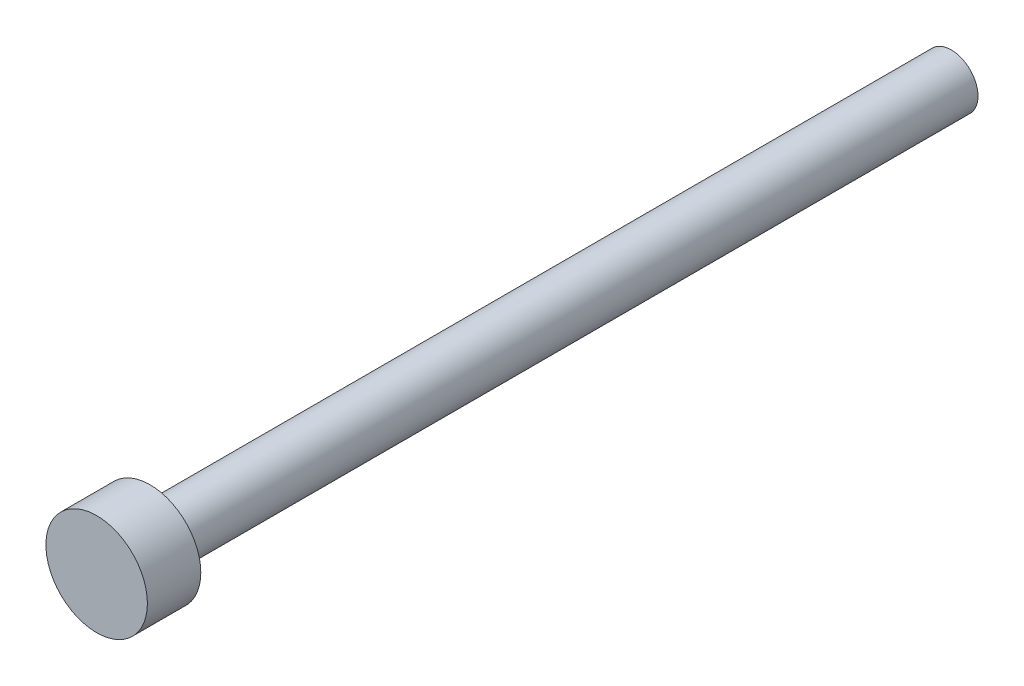
SolidWorks part; units mm, degrees
ref_plane "Front Plane" through (0, 0, 0) normal (0, 0, 1) x (1, 0, 0)
ref_plane "Top Plane" through (0, 0, 0) normal (0, 1, 0) x (1, 0, 0)
ref_plane "Right Plane" through (0, 0, 0) normal (1, 0, 0) x (0, 0, -1)
sketch "Shank_nominal_thread_envelope_profile" plane through (0, 0, 0) normal (0, 0, 1) x (1, 0, 0)
  circle A0 centre (0, 0) radius 1
  dimension "D1" = 2
extrude "Shank_nominal_thread_envelope" add sketch "Shank_nominal_thread_envelope_profile" along normal blind 30 from offset 30
sketch "Socket_head_envelope_profile" plane through (0, 0, 0) normal (0, 0, 1) x (1, 0, 0)
  circle A0 centre (0, 0) radius 1.9
  dimension "D1" = 3.8
extrude "Socket_head_envelope" add sketch "Socket_head_envelope_profile" along normal blind 2
